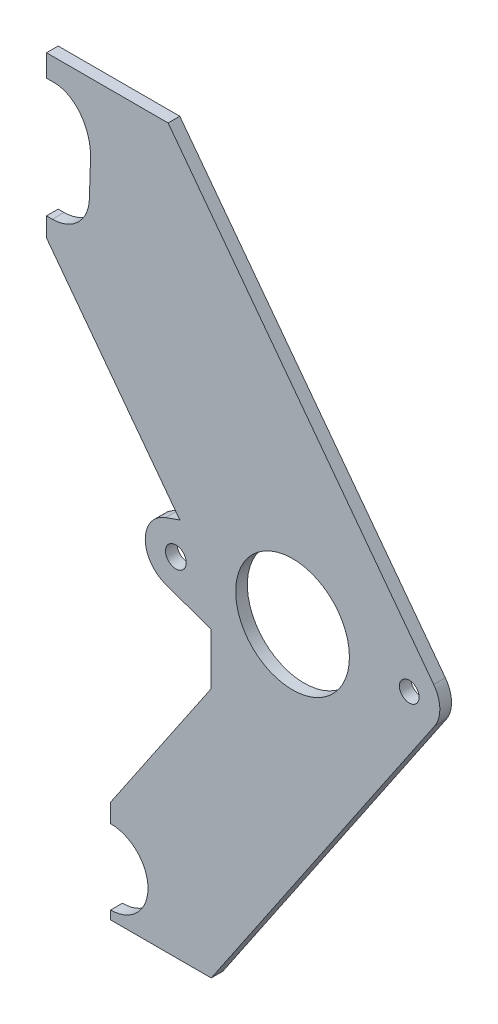
SolidWorks part; units mm, degrees
ref_plane "Front Plane" through (0, 0, 0) normal (0, 0, 1) x (1, 0, 0)
ref_plane "Top Plane" through (0, 0, 0) normal (0, 1, 0) x (1, 0, 0)
ref_plane "Right Plane" through (0, 0, 0) normal (1, 0, 0) x (0, 0, -1)
sketch "Sketch1" plane through (0, 0, 0) normal (0, 0, 1) x (1, 0, 0)
  line L4 (-42.5313, -7.0599) -> (-7.0875, -19.7678)
  line L6 (7.0875, -19.7678) -> (42.5312, -7.0599)
  line L10 (42.5313, 7.0599) -> (7.0875, 19.7678)
  line L12 (-43.5438, -9.8839) -> (-8.1, -22.5918)
  line L13 (8.1, -22.5918) -> (43.5437, -9.8839)
  line L14 (43.5437, 9.8839) -> (8.1, 22.5918)
  line L15 (-8.1, 22.5918) -> (-43.5438, 9.8839)
  line L16 (0, 0) -> (0, -103.21) construction
  line L17 (0, -103.21) -> (-62.35, -103.21) construction
  line L18 (-62.35, -83.9706) -> (-62.35, -90.41)
  line L19 (-62.35, -116.01) -> (-62.35, -118.9706)
  line L20 (-62.35, -118.9706) -> (-27.8815, -118.9706)
  line L21 (-27.8815, -118.9706) -> (48.6942, -5.8874)
  line L22 (-62.35, -83.9706) -> (-27.8815, -33.0692)
  line L23 (-27.8815, -33.0692) -> (-27.8815, -15.4994)
  line L24 (-40, 0) -> (40, 0) construction
  line L25 (0, 0) -> (0, 100) construction
  line L26 (0, 100) -> (-84.35, 100) construction
  line L27 (-84.35, 127.5) -> (-84.35, 72.5)
  line L28 (-84.35, 72.5) -> (-37.5566, 10.2117)
  line L29 (-84.35, 127.5) -> (-42.6503, 127.5)
  line L30 (-42.6503, 127.5) -> (48.395, 6.3067)
  line L32 (-7.0875, 19.7678) -> (-42.5312, 7.0599) construction
  circle A15 centre (-40, 0) radius 3.5658
  circle A16 centre (40, 0) radius 3.3865
  circle A17 centre (0, 0) radius 19.5
  arc A18 (-42.5312, 7.0599) -> (-42.5313, -7.0599) centre (-40, 0) ccw
  arc A19 (-7.0875, -19.7678) -> (7.0875, -19.7678) centre (0, 0) ccw
  arc A20 (42.5312, -7.0599) -> (42.5313, 7.0599) centre (40, 0) ccw
  arc A21 (7.0875, 19.7678) -> (-7.0875, 19.7678) centre (0, 0) ccw
  arc A22 (-8.1, -22.5918) -> (8.1, -22.5918) centre (0, 0) ccw
  arc A23 (43.5437, -9.8839) -> (43.5437, 9.8839) centre (40, 0) ccw
  arc A24 (8.1, 22.5918) -> (-8.1, 22.5918) centre (0, 0) ccw
  arc A25 (-43.5438, 9.8839) -> (-43.5438, -9.8839) centre (-40, 0) ccw
  circle A26 centre (-62.35, -103.21) radius 12.8
  point P36 (-62.35, -103.21)
  point P49 (-84.35, 100)
  dimension "D1" = 39
  dimension "D3" = 3
  dimension "D4" = 103.21
  dimension "D5" = 62.35
  dimension "D6" = 25.6
  dimension "D9" = 22
  dimension "D10" = 55
  dimension "D12" = 40
  dimension "D2" = 80
  dimension "D7" = 35
  dimension "D8" = 100
  dimension "D11" = 40
extrude "Boss-Extrude1" add sketch "Sketch1" along normal blind 4
sketch "Sketch2" plane through (0, 0, 0) normal (0, 0, -1) x (-1, 0, 0)
  line L0 (82.35, 79.0815) -> (84.35, 79.0815)
  line L1 (84.35, 127.5) -> (84.35, 72.5) construction
  line L2 (69.6567, 91.368) -> (69.2547, 103.708)
  line L3 (81.7645, 119.9441) -> (84.35, 119.9441)
  line L4 (84.35, 119.9441) -> (84.35, 79.0815)
  arc A0 (82.35, 104.4815) -> (82.35, 79.0815) centre (82.35, 91.7815) ccw
  arc A1 (69.6567, 91.368) -> (82.35, 79.0815) centre (82.35, 91.7815) ccw
  spline S0 degree 3 poles (70.7283, 96.9027) (65.7505, 108.665) (71.1529, 119.9441) (81.7645, 119.9441) knots 0 0 0 0 1 1 1 1 weights 1 0.680947 0.680947 1
  spline S1 degree 3 poles (69.2547, 103.708) (68.9344, 113.5381) (74.4715, 119.9441) (81.7645, 119.9441) knots 0.236559 0.236559 0.236559 0.236559 1 1 1 1 weights 0.827139 0.698802 0.756422 1
extrude "Cut-Extrude1" cut sketch "Sketch2" against normal up to surface (4 mm away) up to face at (-37.682, -15.8192, 4)
